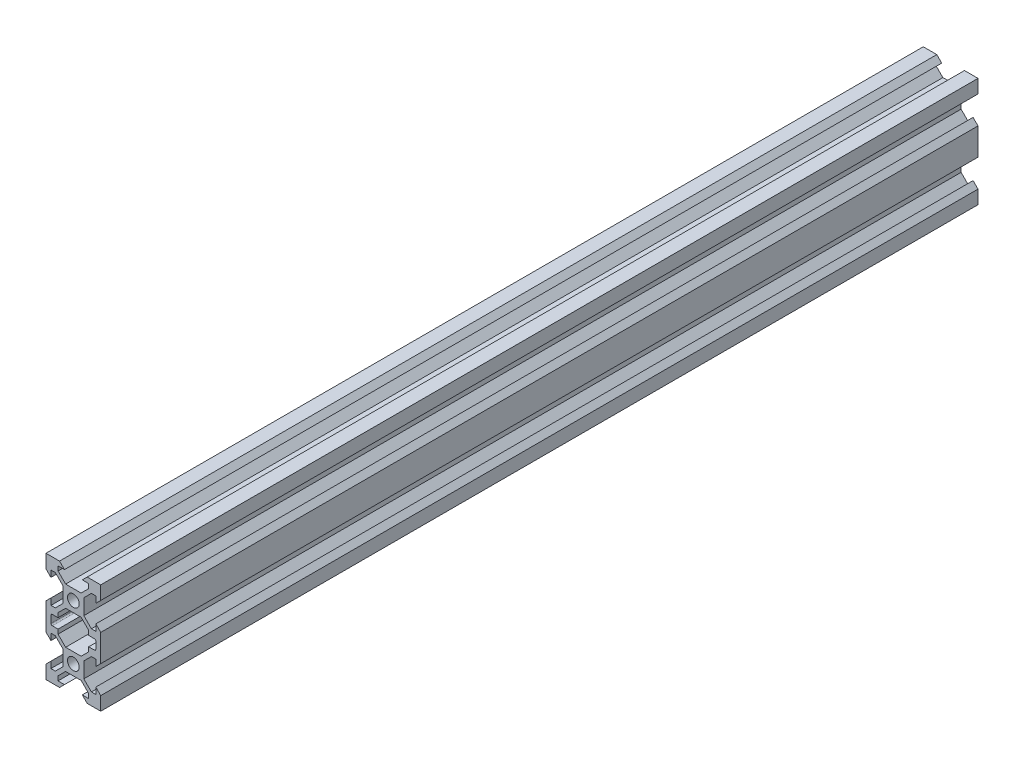
SolidWorks part; units mm, degrees
ref_plane "Alzado" through (0, 0, 0) normal (0, 0, 1) x (1, 0, 0)
ref_plane "Planta" through (0, 0, 0) normal (0, 1, 0) x (1, 0, 0)
ref_plane "Vista lateral" through (0, 0, 0) normal (1, 0, 0) x (0, 0, -1)
sketch "Croquis1" plane through (0, 0, 0) normal (0, 0, 1) x (1, 0, 0)
  line L0 (0, 0) -> (0, -20) construction
  line L2 (0, 0) -> (0, -0.5674)
  line L5 (6.175, -7.1649) -> (6.175, -12.8351)
  line L6 (7.1649, -13.825) -> (12.8351, -13.825)
  line L7 (13.825, -7.1649) -> (13.825, -12.8351)
  line L8 (7.1649, -6.175) -> (12.8351, -6.175)
  line L9 (6.175, -13.825) -> (13.825, -13.825) construction
  line L10 (13.825, -6.175) -> (13.825, -13.825) construction
  line L12 (10, -10) -> (32.1172, -10) construction
  line L13 (13.25, -18.2) -> (15.05, -20)
  line L14 (20, -20) -> (15.6, -20)
  line L15 (20, -20) -> (20, -15.6)
  line L16 (18.2, -15.6) -> (16.5899, -15.6)
  line L32 (15.6, -18.2) -> (15.6, -16.5899)
  line L33 (10, -10) -> (10, -23.2493) construction
  line L34 (4.4, -18.2) -> (4.4, -16.5899)
  line L35 (7.1649, -13.825) -> (4.4, -16.5899)
  line L36 (15.6, -18.2) -> (13.25, -18.2)
  line L38 (15.6, -20) -> (15.05, -20)
  line L40 (15.05, -20) -> (20, -20)
  line L41 (0, -20) -> (20, -20) construction
  line L42 (6.175, -12.8351) -> (3.4101, -15.6)
  line L43 (18.2, -13.25) -> (20, -15.05)
  line L44 (20, -20) -> (18.2, -20)
  line L45 (20, -20) -> (20, -15.05)
  line L48 (20, -15.05) -> (20, -20)
  line L49 (20, 0) -> (20, -20) construction
  line L50 (18.2, -15.6) -> (18.2, -13.25)
  line L51 (12.8351, -13.825) -> (15.6, -16.5899)
  line L52 (13.825, -12.8351) -> (16.5899, -15.6)
  line L53 (1.8, -15.6) -> (3.4101, -15.6)
  line L54 (1.8, -15.6) -> (1.8, -13.25)
  line L55 (1.8, -13.25) -> (0, -15.05)
  line L56 (0, 0) -> (20, 0) construction
  line L57 (0, -20) -> (0, -15.6)
  line L58 (0, -15.6) -> (0, -15.05)
  line L59 (0, -20) -> (4.4, -20)
  line L60 (0, -20) -> (4.95, -20)
  line L61 (6.75, -18.2) -> (4.95, -20)
  line L62 (4.4, -18.2) -> (6.75, -18.2)
  line L63 (1.8, -4.4) -> (3.4101, -4.4)
  line L64 (6.175, -7.1649) -> (3.4101, -4.4)
  line L65 (7.1649, -6.175) -> (4.4, -3.4101)
  line L66 (4.4, -1.8) -> (4.4, -3.4101)
  line L71 (0, 0) -> (0, -4.4)
  line L72 (0, 0) -> (0, -4.95)
  line L73 (1.8, -6.75) -> (0, -4.95)
  line L74 (1.8, -4.4) -> (1.8, -6.75)
  line L75 (15.6, -1.8) -> (15.6, -3.4101)
  line L76 (12.8351, -6.175) -> (15.6, -3.4101)
  line L77 (13.825, -7.1649) -> (16.5899, -4.4)
  line L78 (18.2, -4.4) -> (16.5899, -4.4)
  line L79 (18.2, -4.4) -> (18.2, -6.75)
  line L80 (18.2, -6.75) -> (20, -4.95)
  line L81 (20, 0) -> (20, -4.4)
  line L82 (20, -4.4) -> (20, -4.95)
  line L87 (6.175, -6.175) -> (13.825, -6.175) construction
  line L88 (6.175, -6.175) -> (6.175, -13.825) construction
  line L89 (0, 20) -> (0, 19.4326)
  line L90 (6.175, 12.8351) -> (6.175, 7.1649)
  line L91 (7.1649, 6.175) -> (12.8351, 6.175)
  line L92 (13.825, 12.8351) -> (13.825, 7.1649)
  line L93 (7.1649, 13.825) -> (12.8351, 13.825)
  line L96 (20, 0) -> (20, 4.4)
  line L97 (18.2, 4.4) -> (16.5899, 4.4)
  line L98 (15.6, 1.8) -> (15.6, 3.4101)
  line L99 (4.4, 1.8) -> (4.4, 3.4101)
  line L100 (7.1649, 6.175) -> (4.4, 3.4101)
  line L104 (6.175, 7.1649) -> (3.4101, 4.4)
  line L105 (18.2, 6.75) -> (20, 4.95)
  line L107 (20, 0) -> (20, 4.95)
  line L108 (20, 4.95) -> (20, 0)
  line L109 (18.2, 4.4) -> (18.2, 6.75)
  line L110 (12.8351, 6.175) -> (15.6, 3.4101)
  line L111 (13.825, 7.1649) -> (16.5899, 4.4)
  line L112 (1.8, 4.4) -> (3.4101, 4.4)
  line L113 (1.8, 4.4) -> (1.8, 6.75)
  line L114 (1.8, 6.75) -> (0, 4.95)
  line L115 (0, 0) -> (0, 4.4)
  line L116 (0, 4.4) -> (0, 4.95)
  line L121 (1.8, 15.6) -> (3.4101, 15.6)
  line L122 (6.175, 12.8351) -> (3.4101, 15.6)
  line L123 (7.1649, 13.825) -> (4.4, 16.5899)
  line L124 (4.4, 18.2) -> (4.4, 16.5899)
  line L125 (4.4, 18.2) -> (6.75, 18.2)
  line L126 (6.75, 18.2) -> (4.95, 20)
  line L127 (0, 20) -> (4.4, 20)
  line L128 (4.4, 20) -> (4.95, 20)
  line L129 (0, 20) -> (0, 15.6)
  line L130 (0, 20) -> (0, 15.05)
  line L131 (1.8, 13.25) -> (0, 15.05)
  line L132 (1.8, 15.6) -> (1.8, 13.25)
  line L133 (15.6, 18.2) -> (15.6, 16.5899)
  line L134 (12.8351, 13.825) -> (15.6, 16.5899)
  line L135 (13.825, 12.8351) -> (16.5899, 15.6)
  line L136 (18.2, 15.6) -> (16.5899, 15.6)
  line L137 (18.2, 15.6) -> (18.2, 13.25)
  line L138 (18.2, 13.25) -> (20, 15.05)
  line L139 (20, 20) -> (20, 15.6)
  line L140 (20, 15.6) -> (20, 15.05)
  line L141 (20, 20) -> (15.6, 20)
  line L142 (20, 20) -> (15.05, 20)
  line L143 (13.25, 18.2) -> (15.05, 20)
  line L144 (15.6, 18.2) -> (13.25, 18.2)
  line L146 (4.4, 1.8) -> (2.3, 1.8)
  line L147 (10, 10) -> (10, -3.2493) construction
  line L148 (10, 10) -> (32.1172, 10) construction
  line L150 (4.4, -1.8) -> (2.3, -1.8)
  line L151 (1.8, 1.3) -> (1.8, -1.3)
  line L152 (15.6, -1.8) -> (17.7, -1.8)
  line L154 (15.6, 1.8) -> (17.7, 1.8)
  line L155 (18.2, -1.3) -> (18.2, 1.3)
  line L156 (4.4, 1.8) -> (6.75, 1.8) [skipped]
  line L157 (6.75, 1.8) -> (4.95, 0) [skipped]
  line L158 (6.75, -1.8) -> (4.95, 0) [skipped]
  line L159 (4.4, -1.8) -> (6.75, -1.8) [skipped]
  line L160 (15.6, -1.8) -> (13.25, -1.8) [skipped]
  line L161 (13.25, -1.8) -> (15.05, 0) [skipped]
  line L162 (13.25, 1.8) -> (15.05, 0) [skipped]
  line L163 (15.6, 1.8) -> (13.25, 1.8) [skipped]
  line L164 (15.6, 0) -> (15.05, 0) [skipped]
  line L165 (4.4, 0) -> (4.95, 0) [skipped]
  line L166 (20, 0) -> (18.2, 0) [skipped]
  line L167 (18.2, 0) -> (20, 0) [skipped]
  line L168 (20, 0) -> (18.2, 0) [skipped]
  line L169 (20, 0) -> (18.2, 0) [skipped]
  line L170 (20, 0) -> (18.2, 0) [skipped]
  line L171 (0, 0) -> (1.8, 0) [skipped]
  line L172 (0, 0) -> (1.8, 0) [skipped]
  line L173 (0, 0) -> (1.8, 0) [skipped]
  circle A0 centre (10, -10) radius 2.15
  circle A1 centre (10, 10) radius 2.15
  arc A2 (17.7, 1.8) -> (18.2, 1.3) centre (17.7, 1.3) cw
  arc A3 (17.7, -1.8) -> (18.2, -1.3) centre (17.7, -1.3) ccw
  arc A4 (2.3, -1.8) -> (1.8, -1.3) centre (2.3, -1.3) cw
  arc A5 (2.3, 1.8) -> (1.8, 1.3) centre (2.3, 1.3) ccw
  point P69 (10, -10)
  point P128 (10, 10)
  dimension "D3" = 4.3
  dimension "D5" = 0.5
  dimension "D2" = 4
  dimension "D4" = 2
  dimension "D11" = 4.4
  dimension "D15" = 4.4
  dimension "D16" = 6.75
extrude "Saliente-Extruir1" add sketch "Croquis1" along normal blind 320.6 contours L144 L133 L134 L93 L123 L124 L125 L126 L128 L127 L89 L129 L130 L131 L132 L121 L122 L90 L104 L112 L113 L114 L116 L115 L2 L71 L72 L73 L74 L63 L64 L5 L42 L53 L54 L55 L58 L57 L59 L60 L61 L62 L34 L35 L6 L51 L32 L36 L13 L38 L40
